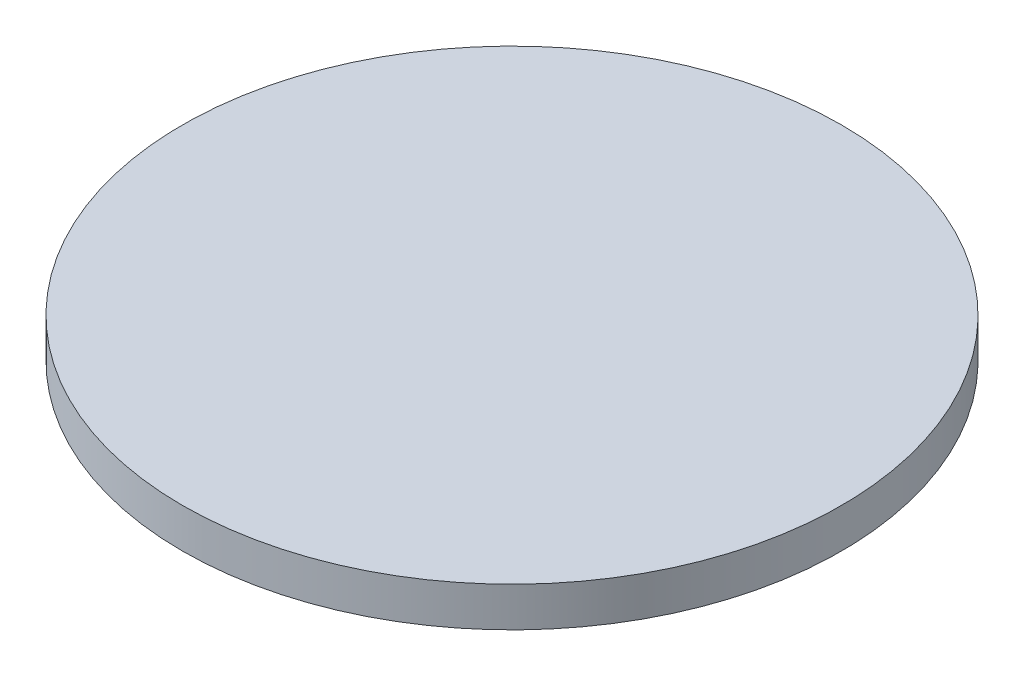
SolidWorks part; units mm, degrees
ref_plane "Front Plane" through (0, 0, 0) normal (0, 0, 1) x (1, 0, 0)
ref_plane "Top Plane" through (0, 0, 0) normal (0, 1, 0) x (1, 0, 0)
ref_plane "Right Plane" through (0, 0, 0) normal (1, 0, 0) x (0, 0, -1)
sketch "Sketch1" plane through (0, 0, 0) normal (0, 1, 0) x (1, 0, 0)
  circle A0 centre (0, 0.2572) radius 2.5
  dimension "D1" = 5
extrude "Boss-Extrude1" add sketch "Sketch1" along normal blind 0.3
